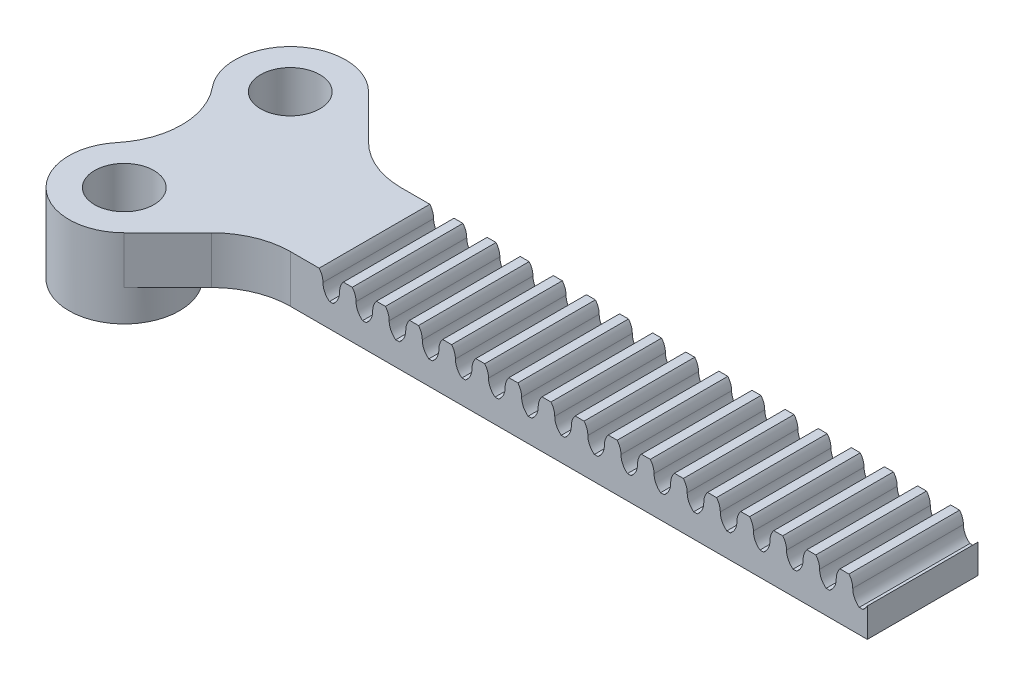
SolidWorks part; units mm, degrees
ref_plane "Alzado" through (0, 0, 0) normal (0, 0, 1) x (1, 0, 0)
ref_plane "Planta" through (0, 0, 0) normal (0, 1, 0) x (1, 0, 0)
ref_plane "Vista lateral" through (0, 0, 0) normal (1, 0, 0) x (0, 0, -1)
sketch "Croquis14" plane through (0, 0, 0) normal (0, 1, 0) x (1, 0, 0)
  line L0 (0, 0) -> (-80, 0) construction
  line L1 (-80, 0) -> (-90.5, 10.5) construction
  line L2 (-80, 0) -> (-90.5, -10.5) construction
  line L3 (0, 7) -> (-72.9584, 7)
  line L6 (-80.0294, 9.9289) -> (-85.5503, 15.4497)
  line L10 (0, 7) -> (0, -7)
  line L11 (0, -7) -> (-72.9584, -7)
  line L12 (-80.0294, -9.9289) -> (-85.5503, -15.4497)
  arc A4 (-85.5503, 15.4497) -> (-95.9012, 6.0472) centre (-90.5, 10.5) ccw
  arc A5 (-85.5503, -15.4497) -> (-95.9012, -6.0472) centre (-90.5, -10.5) cw
  arc A6 (-72.9584, -7) -> (-80.0294, -9.9289) centre (-72.9584, -17) ccw
  arc A7 (-72.9584, 7) -> (-80.0294, 9.9289) centre (-72.9584, 17) cw
  arc A9 (-95.9012, 6.0472) -> (-95.9012, -6.0472) centre (-103.2364, 0) cw
  point P4 (-93.7299, 0)
  point P11 (-90.0777, 0)
  point P12 (-97.8455, 0)
  point P22 (-77.1005, -7)
  point P25 (-77.1005, 7)
  dimension "D6" = 10
  dimension "D7" = 7
  dimension "D1" = 80
  dimension "D2" = 135
  dimension "D3" = 21
  dimension "D4" = 7
  dimension "D5" = 13.7299
extrude "Saliente-Extruir1" add sketch "Croquis14" along normal blind 6
sketch "Croquis16" plane through (0, 0, 7) normal (0, 0, 1) x (1, 0, 0)
  line L4 (-72.9584, 6) -> (-70.9584, 6) construction
  line L5 (-63.8511, 2.9991) -> (-63.4004, 2.9991)
  line L6 (-72.9584, 6) -> (0, 6) construction
  line L7 (-70.9584, 6) -> (-70.9584, 3) construction
  line L8 (-65.1545, 6) -> (-62.0984, 6)
  line L9 (-59.6624, 2.9991) -> (-59.2117, 2.9991)
  line L10 (-60.9658, 6) -> (-57.9097, 6)
  line L11 (-68.0398, 2.9991) -> (-67.5891, 2.9991)
  line L12 (-68.0398, 2.9991) -> (-67.5891, 2.9991) construction
  line L13 (-69.3432, 6) -> (-66.2871, 6)
  line L14 (-55.4737, 2.9991) -> (-55.023, 2.9991)
  line L15 (-62.9584, 3) -> (0, 3) construction
  line L16 (-56.7771, 6) -> (-53.721, 6)
  line L17 (-51.285, 2.9991) -> (-50.8343, 2.9991)
  line L18 (-52.5884, 6) -> (-49.5323, 6)
  line L19 (-47.0963, 2.9991) -> (-46.6456, 2.9991)
  line L20 (-48.3997, 6) -> (-45.3436, 6)
  line L21 (-42.9076, 2.9991) -> (-42.4569, 2.9991)
  line L22 (-44.211, 6) -> (-41.1549, 6)
  line L23 (-38.7189, 2.9991) -> (-38.2682, 2.9991)
  line L24 (-40.0223, 6) -> (-36.9662, 6)
  line L25 (-34.5302, 2.9991) -> (-34.0795, 2.9991)
  line L26 (-35.8336, 6) -> (-32.7775, 6)
  line L27 (-30.3415, 2.9991) -> (-29.8908, 2.9991)
  line L28 (-31.6449, 6) -> (-28.5888, 6)
  line L29 (-26.1528, 2.9991) -> (-25.7021, 2.9991)
  line L30 (-27.4562, 6) -> (-24.4001, 6)
  line L31 (-21.9641, 2.9991) -> (-21.5134, 2.9991)
  line L32 (-23.2675, 6) -> (-20.2114, 6)
  line L33 (-17.7754, 2.9991) -> (-17.3247, 2.9991)
  line L34 (-19.0788, 6) -> (-16.0227, 6)
  line L35 (-13.5867, 2.9991) -> (-13.136, 2.9991)
  line L36 (-14.8901, 6) -> (-11.834, 6)
  line L37 (-9.398, 2.9991) -> (-8.9473, 2.9991)
  line L38 (-10.7014, 6) -> (-7.6453, 6)
  line L39 (-5.2093, 2.9991) -> (-4.7586, 2.9991)
  line L40 (-6.5127, 6) -> (-3.4566, 6)
  line L41 (-1.0206, 2.9991) -> (-0.5699, 2.9991)
  line L42 (-2.324, 6) -> (0.7321, 6)
  arc A0 (-68.864, 4.6667) -> (-69.3432, 6) centre (-70.9584, 4.6667) ccw
  arc A2 (-68.864, 4.6667) -> (-68.0398, 2.9991) centre (-66.7649, 4.6667) ccw
  arc A4 (-67.5891, 2.9991) -> (-66.7649, 4.6667) centre (-68.864, 4.6667) ccw
  arc A5 (-63.4004, 2.9991) -> (-62.5762, 4.6667) centre (-64.6753, 4.6667) ccw
  arc A6 (-64.6753, 4.6667) -> (-63.8511, 2.9991) centre (-62.5762, 4.6667) ccw
  arc A7 (-62.0984, 6) -> (-62.5762, 4.6667) centre (-60.4771, 4.6667) ccw
  arc A8 (-66.2871, 6) -> (-66.7649, 4.6667) centre (-64.6658, 4.6667) ccw
  arc A9 (-64.6753, 4.6667) -> (-65.1545, 6) centre (-66.7697, 4.6667) ccw
  arc A10 (-59.2117, 2.9991) -> (-58.3875, 4.6667) centre (-60.4866, 4.6667) ccw
  arc A11 (-60.4866, 4.6667) -> (-59.6624, 2.9991) centre (-58.3875, 4.6667) ccw
  arc A12 (-57.9097, 6) -> (-58.3875, 4.6667) centre (-56.2884, 4.6667) ccw
  arc A13 (-60.4866, 4.6667) -> (-60.9658, 6) centre (-62.581, 4.6667) ccw
  arc A14 (-55.023, 2.9991) -> (-54.1988, 4.6667) centre (-56.2979, 4.6667) ccw
  arc A15 (-56.2979, 4.6667) -> (-55.4737, 2.9991) centre (-54.1988, 4.6667) ccw
  arc A16 (-53.721, 6) -> (-54.1988, 4.6667) centre (-52.0997, 4.6667) ccw
  arc A17 (-56.2979, 4.6667) -> (-56.7771, 6) centre (-58.3923, 4.6667) ccw
  arc A18 (-50.8343, 2.9991) -> (-50.0101, 4.6667) centre (-52.1092, 4.6667) ccw
  arc A19 (-52.1092, 4.6667) -> (-51.285, 2.9991) centre (-50.0101, 4.6667) ccw
  arc A20 (-49.5323, 6) -> (-50.0101, 4.6667) centre (-47.911, 4.6667) ccw
  arc A21 (-52.1092, 4.6667) -> (-52.5884, 6) centre (-54.2036, 4.6667) ccw
  arc A22 (-46.6456, 2.9991) -> (-45.8214, 4.6667) centre (-47.9205, 4.6667) ccw
  arc A23 (-47.9205, 4.6667) -> (-47.0963, 2.9991) centre (-45.8214, 4.6667) ccw
  arc A24 (-45.3436, 6) -> (-45.8214, 4.6667) centre (-43.7223, 4.6667) ccw
  arc A25 (-47.9205, 4.6667) -> (-48.3997, 6) centre (-50.0149, 4.6667) ccw
  arc A26 (-42.4569, 2.9991) -> (-41.6327, 4.6667) centre (-43.7318, 4.6667) ccw
  arc A27 (-43.7318, 4.6667) -> (-42.9076, 2.9991) centre (-41.6327, 4.6667) ccw
  arc A28 (-41.1549, 6) -> (-41.6327, 4.6667) centre (-39.5336, 4.6667) ccw
  arc A29 (-43.7318, 4.6667) -> (-44.211, 6) centre (-45.8262, 4.6667) ccw
  arc A30 (-38.2682, 2.9991) -> (-37.444, 4.6667) centre (-39.5431, 4.6667) ccw
  arc A31 (-39.5431, 4.6667) -> (-38.7189, 2.9991) centre (-37.444, 4.6667) ccw
  arc A32 (-36.9662, 6) -> (-37.444, 4.6667) centre (-35.3449, 4.6667) ccw
  arc A33 (-39.5431, 4.6667) -> (-40.0223, 6) centre (-41.6375, 4.6667) ccw
  arc A34 (-34.0795, 2.9991) -> (-33.2553, 4.6667) centre (-35.3544, 4.6667) ccw
  arc A35 (-35.3544, 4.6667) -> (-34.5302, 2.9991) centre (-33.2553, 4.6667) ccw
  arc A36 (-32.7775, 6) -> (-33.2553, 4.6667) centre (-31.1562, 4.6667) ccw
  arc A37 (-35.3544, 4.6667) -> (-35.8336, 6) centre (-37.4488, 4.6667) ccw
  arc A38 (-29.8908, 2.9991) -> (-29.0666, 4.6667) centre (-31.1657, 4.6667) ccw
  arc A39 (-31.1657, 4.6667) -> (-30.3415, 2.9991) centre (-29.0666, 4.6667) ccw
  arc A40 (-28.5888, 6) -> (-29.0666, 4.6667) centre (-26.9675, 4.6667) ccw
  arc A41 (-31.1657, 4.6667) -> (-31.6449, 6) centre (-33.2601, 4.6667) ccw
  arc A42 (-25.7021, 2.9991) -> (-24.8779, 4.6667) centre (-26.977, 4.6667) ccw
  arc A43 (-26.977, 4.6667) -> (-26.1528, 2.9991) centre (-24.8779, 4.6667) ccw
  arc A44 (-24.4001, 6) -> (-24.8779, 4.6667) centre (-22.7788, 4.6667) ccw
  arc A45 (-26.977, 4.6667) -> (-27.4562, 6) centre (-29.0714, 4.6667) ccw
  arc A46 (-21.5134, 2.9991) -> (-20.6892, 4.6667) centre (-22.7883, 4.6667) ccw
  arc A47 (-22.7883, 4.6667) -> (-21.9641, 2.9991) centre (-20.6892, 4.6667) ccw
  arc A48 (-20.2114, 6) -> (-20.6892, 4.6667) centre (-18.5901, 4.6667) ccw
  arc A49 (-22.7883, 4.6667) -> (-23.2675, 6) centre (-24.8827, 4.6667) ccw
  arc A50 (-17.3247, 2.9991) -> (-16.5005, 4.6667) centre (-18.5996, 4.6667) ccw
  arc A51 (-18.5996, 4.6667) -> (-17.7754, 2.9991) centre (-16.5005, 4.6667) ccw
  arc A52 (-16.0227, 6) -> (-16.5005, 4.6667) centre (-14.4014, 4.6667) ccw
  arc A53 (-18.5996, 4.6667) -> (-19.0788, 6) centre (-20.694, 4.6667) ccw
  arc A54 (-13.136, 2.9991) -> (-12.3118, 4.6667) centre (-14.4109, 4.6667) ccw
  arc A55 (-14.4109, 4.6667) -> (-13.5867, 2.9991) centre (-12.3118, 4.6667) ccw
  arc A56 (-11.834, 6) -> (-12.3118, 4.6667) centre (-10.2127, 4.6667) ccw
  arc A57 (-14.4109, 4.6667) -> (-14.8901, 6) centre (-16.5053, 4.6667) ccw
  arc A58 (-8.9473, 2.9991) -> (-8.1231, 4.6667) centre (-10.2222, 4.6667) ccw
  arc A59 (-10.2222, 4.6667) -> (-9.398, 2.9991) centre (-8.1231, 4.6667) ccw
  arc A60 (-7.6453, 6) -> (-8.1231, 4.6667) centre (-6.024, 4.6667) ccw
  arc A61 (-10.2222, 4.6667) -> (-10.7014, 6) centre (-12.3166, 4.6667) ccw
  arc A62 (-4.7586, 2.9991) -> (-3.9344, 4.6667) centre (-6.0335, 4.6667) ccw
  arc A63 (-6.0335, 4.6667) -> (-5.2093, 2.9991) centre (-3.9344, 4.6667) ccw
  arc A64 (-3.4566, 6) -> (-3.9344, 4.6667) centre (-1.8353, 4.6667) ccw
  arc A65 (-6.0335, 4.6667) -> (-6.5127, 6) centre (-8.1279, 4.6667) ccw
  arc A66 (-0.5699, 2.9991) -> (0.2543, 4.6667) centre (-1.8448, 4.6667) ccw
  arc A67 (-1.8448, 4.6667) -> (-1.0206, 2.9991) centre (0.2543, 4.6667) ccw
  arc A68 (0.7321, 6) -> (0.2543, 4.6667) centre (2.3534, 4.6667) ccw
  arc A69 (-1.8448, 4.6667) -> (-2.324, 6) centre (-3.9392, 4.6667) ccw
  dimension "D4" = 4.1887
  dimension "D1" = 2
  dimension "D2" = 3
  dimension "D3" = 1.3333
  dimension "D5" = 8
  dimension "D6" = 6.2925
  dimension "D7" = 0.4507
  dimension "D8" = 1.6151
  dimension "D9" = 17
sketch "Croquis18" plane through (0, 6, 0) normal (0, 1, 0) x (1, 0, 0)
  line L0 (0, 0) -> (-119.6208, 0) construction
  circle A0 centre (-90.5, -10.5) radius 3.75
  circle A1 centre (-90.5, 10.5) radius 3.75
  dimension "D1" = 7.5
extrude "Cortar-Extruir2" cut sketch "Croquis18" against normal through all
extrude "Cortar-Extruir3" cut sketch "Croquis16" against normal through all
sketch "Croquis21" plane through (0, 0, 0) normal (0, -1, 0) x (1, 0, 0)
  line L0 (-93.7299, 0) -> (-84.9834, 0) construction
  circle A0 centre (-90.5, -10.5) radius 3.75
  circle A1 centre (-90.5, -10.5) radius 7
  arc A3 (-95.9012, -6.0472) -> (-85.5503, -15.4497) centre (-90.5, -10.5) ccw construction
  circle A4 centre (-90.5, -10.5) radius 3.75 construction
  arc A5 (-95.9012, -6.0472) -> (-95.9012, 6.0472) centre (-103.2364, 0) ccw construction
  circle A6 centre (-90.5, 10.5) radius 3.75
  circle A7 centre (-90.5, 10.5) radius 7
extrude "Saliente-Extruir3" add sketch "Croquis21" along normal blind 4
